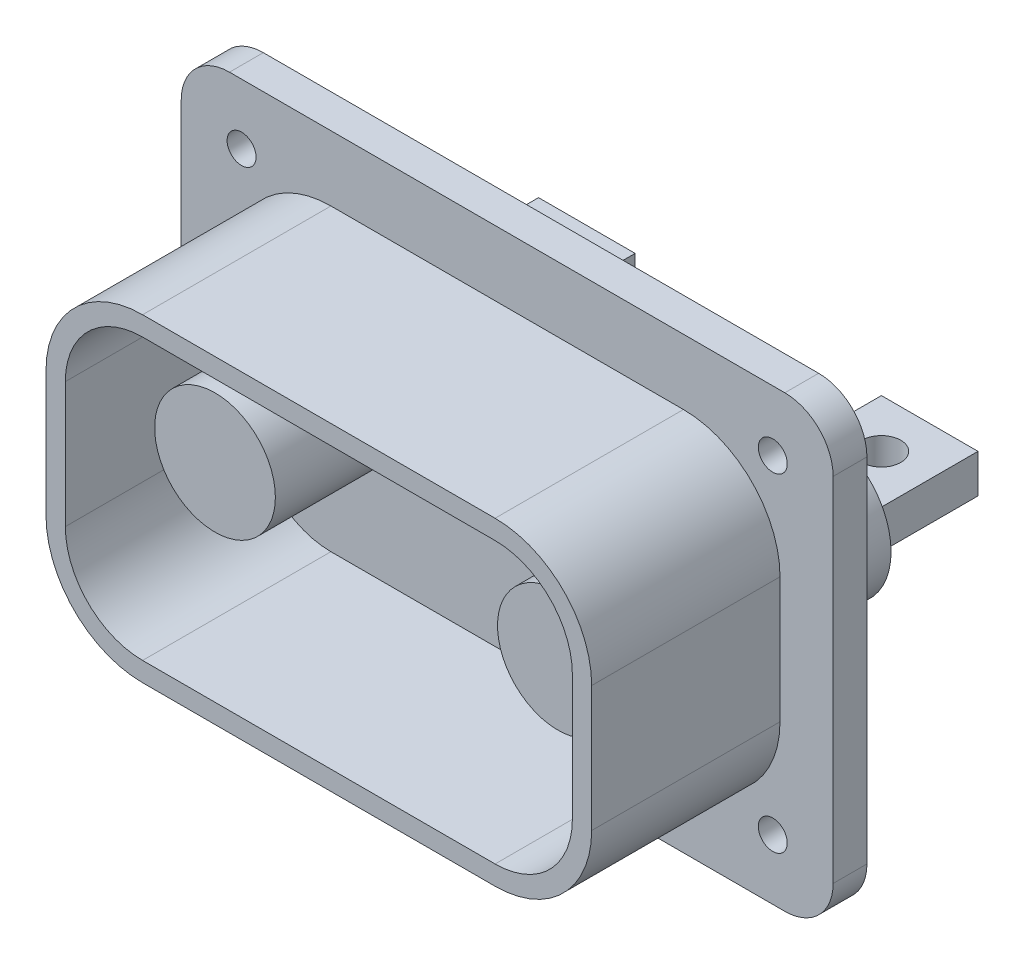
SolidWorks part; units mm, degrees
material "Custom Plastic"
ref_plane "X-Y Datum" through (0, 0, 0) normal (0, 0, 1) x (1, 0, 0)
ref_plane "X-Z Datum" through (0, 0, 0) normal (0, 1, 0) x (1, 0, 0)
ref_plane "Y-Z Datum" through (0, 0, 0) normal (1, 0, 0) x (0, 0, -1)
sketch "Sketch1" plane through (0, 0, 0) normal (0, 0, 1) x (1, 0, 0)
  line L1 (-67.5, -46.5) -> (67.5, -46.5)
  line L2 (-67.5, -46.5) -> (-67.5, 46.5)
  line L3 (-67.5, 46.5) -> (67.5, 46.5)
  line L4 (67.5, -46.5) -> (67.5, 46.5)
  line L5 (-67.5, -46.5) -> (67.5, 46.5) construction
  line L6 (-67.5, 46.5) -> (67.5, -46.5) construction
  line L11 (-50.4972, -34.787) -> (50.4972, 34.787) construction
  line L12 (-50.4972, 34.787) -> (50.4972, -34.787) construction
  line L13 (-55, 34) -> (55, 34) construction
  line L14 (-55, 34) -> (-55, -34) construction
  line L15 (-55, -34) -> (55, -34) construction
  line L16 (55, 34) -> (55, -34) construction
  line L17 (-55, 34) -> (55, -34) construction
  line L18 (-55, -34) -> (55, 34) construction
  circle A4 centre (-55, 34) radius 3
  circle A5 centre (55, 34) radius 3
  circle A6 centre (55, -34) radius 3
  circle A7 centre (-55, -34) radius 3
  point P0 (0, 0)
  point P6 (0, 0)
  point P12 (0, 0)
  dimension "D3" = 110
  dimension "D4" = 68
  dimension "D5" = 6
  dimension "D1" = 135
  dimension "D2" = 93
extrude "Boss-Extrude1" add sketch "Sketch1" along normal blind 7
sketch "Sketch2" plane through (0, 0, 7) normal (0, 0, 1) x (1, 0, 0)
  line L0 (-35.5, 0) -> (35.5, 0) construction
  line L5 (-52.5, 13) -> (-52.5, -13)
  line L6 (-36.5, 33) -> (36.5, 33)
  line L7 (-56.5, 13) -> (-56.5, -13)
  line L8 (-36.5, -33) -> (36.5, -33)
  line L9 (56.5, 13) -> (56.5, -13)
  line L10 (-56.5, 33) -> (56.5, -33) construction
  line L11 (-56.5, -33) -> (56.5, 33) construction
  line L12 (-36.5, -29) -> (36.5, -29)
  line L13 (52.5, 13) -> (52.5, -13)
  line L14 (-36.5, 29) -> (36.5, 29)
  circle A4 centre (-35.5, 0) radius 4 construction
  circle A5 centre (35.5, 0) radius 4 construction
  arc A6 (36.5, -33) -> (56.5, -13) centre (36.5, -13) ccw
  arc A7 (36.5, 33) -> (56.5, 13) centre (36.5, 13) cw
  arc A8 (-36.5, 33) -> (-56.5, 13) centre (-36.5, 13) ccw
  arc A9 (-56.5, -13) -> (-36.5, -33) centre (-36.5, -13) ccw
  arc A10 (-52.5, -13) -> (-36.5, -29) centre (-36.5, -13) ccw
  arc A11 (36.5, -29) -> (52.5, -13) centre (36.5, -13) ccw
  arc A12 (36.5, 29) -> (52.5, 13) centre (36.5, 13) cw
  arc A13 (-36.5, 29) -> (-52.5, 13) centre (-36.5, 13) ccw
  point P2 (0, 0)
  point P4 (0, 0)
  dimension "D1" = 8
  dimension "D5" = 20
  dimension "D2" = 71
  dimension "D3" = 113
  dimension "D4" = 66
  dimension "D6" = 4
extrude "Boss-Extrude2" add sketch "Sketch2" along normal blind 39
fillet "Fillet1" radius 10 4 edges at (67.5, 46.5, 3.5) (67.5, -46.5, 3.5) (-67.5, -46.5, 3.5) (-67.5, 46.5, 3.5)
sketch "Sketch3" plane through (0, 0, 0) normal (0, 0, -1) x (-1, 0, 0)
  line L0 (-35.5, 0) -> (35.5, 0) construction
  circle A0 centre (-35.5, 0) radius 15
  circle A1 centre (35.5, 0) radius 15
  point P11 (0, 0)
  dimension "D1" = 71
  dimension "D2" = 30
extrude "Boss-Extrude3" add sketch "Sketch3" along normal blind 22
sketch "Sketch5" plane through (0, 0, -22) normal (0, 0, -1) x (-1, 0, 0)
  line L1 (-45.5, 4) -> (-25.5, 4)
  line L2 (-45.5, 4) -> (-45.5, -4)
  line L3 (-45.5, -4) -> (-25.5, -4)
  line L4 (-25.5, 4) -> (-25.5, -4)
  line L5 (-45.5, 4) -> (-25.5, -4) construction
  line L6 (-45.5, -4) -> (-25.5, 4) construction
  line L7 (25.5, 4) -> (45.5, 4)
  line L8 (25.5, 4) -> (25.5, -4)
  line L9 (25.5, -4) -> (45.5, -4)
  line L10 (45.5, 4) -> (45.5, -4)
  line L11 (25.5, 4) -> (45.5, -4) construction
  line L12 (25.5, -4) -> (45.5, 4) construction
  point P0 (-35.5, 0)
  point P6 (35.5, 0)
  dimension "D1" = 8
  dimension "D2" = 20
extrude "Boss-Extrude4" add sketch "Sketch5" along normal blind 23
sketch "Sketch6" plane through (0, 4, 0) normal (0, 1, 0) x (1, 0, 0)
  line L0 (35.5, 45) -> (35.5, 22) construction
  line L1 (25.5, 45) -> (45.5, 45) construction
  line L2 (50.5, 22) -> (20.5, 22) construction
  line L3 (0, -43.0151) -> (0, 43.0151) construction
  circle A0 centre (35.5, 35) radius 4
  circle A1 centre (-35.5, 35) radius 4
  dimension "D1" = 8
  dimension "D2" = 10
extrude "Cut-Extrude1" cut sketch "Sketch6" against normal through all
sketch "Sketch7" plane through (0, 0, 7) normal (0, 0, 1) x (1, 0, 0)
  line L0 (-35.5, 0) -> (35.5, 0) construction
  circle A0 centre (-35.5, 0) radius 12.5
  circle A1 centre (35.5, 0) radius 12.5
  point P4 (0, 0)
  dimension "D2" = 25
  dimension "D1" = 71
extrude "Boss-Extrude5" add sketch "Sketch7" along normal blind 25
